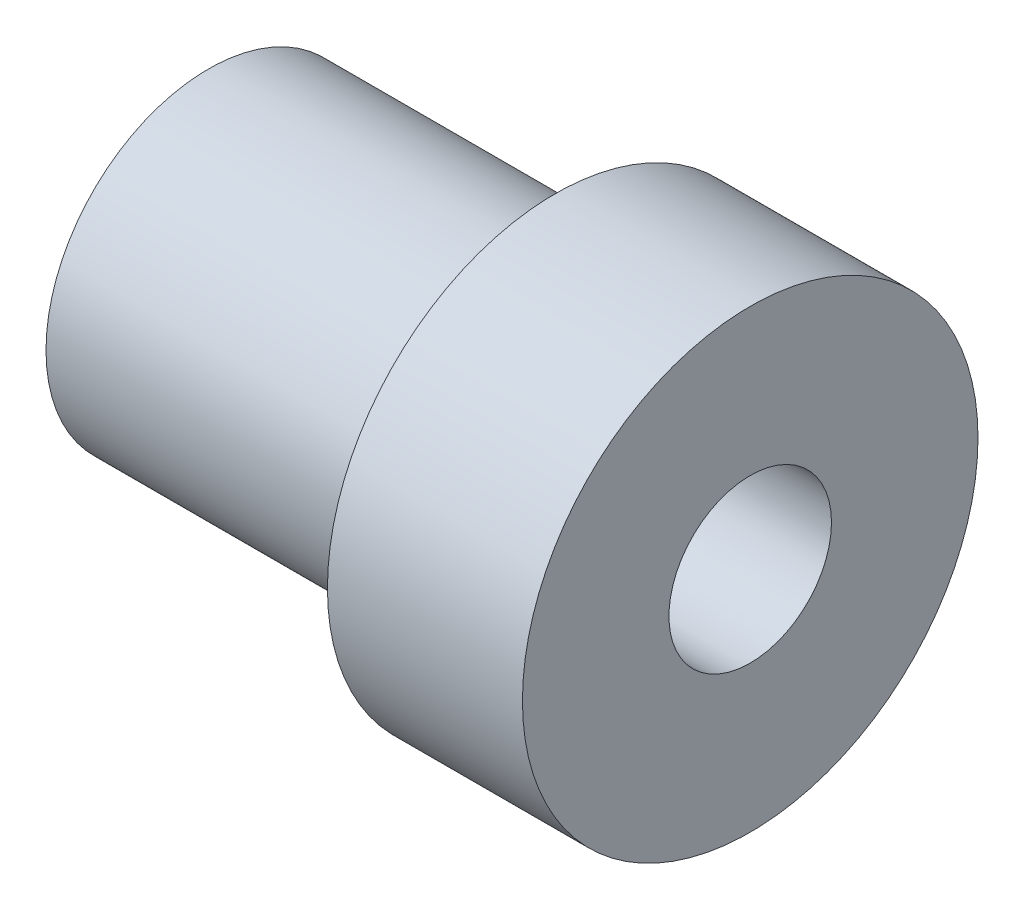
SolidWorks part; units mm, degrees
ref_plane "Front Plane" through (0, 0, 0) normal (0, 0, 1) x (1, 0, 0)
ref_plane "Top Plane" through (0, 0, 0) normal (0, 1, 0) x (1, 0, 0)
ref_plane "Right Plane" through (0, 0, 0) normal (1, 0, 0) x (0, 0, -1)
sketch "Sketch1" plane through (0, 0, 0) normal (1, 0, 0) x (0, 0, -1)
  circle A0 centre (0, 0) radius 3.9688
  dimension "D1" = 7.9375
extrude "Boss-Extrude1" add sketch "Sketch1" along normal blind 8.4667
sketch "Sketch2" plane through (8.4667, 0, 0) normal (1, 0, 0) x (0, 0, -1)
  circle A0 centre (0, 0) radius 5.5626
  dimension "D1" = 11.1252
extrude "Boss-Extrude2" add sketch "Sketch2" along normal blind 4.7625
hole_wizard "5/32 (0.15625) Diameter Hole1" positions "Sketch4" profile "Sketch3" hole size "5/32" standard "ANSI Inch"
sketch "Sketch4" plane through (13.2292, 0, 0) normal (1, 0, 0) x (0, 0, -1)
  point P0 (0, 0)
sketch "Sketch3" plane through (13.2292, 0, 0) normal (0, 1, 0) x (0, 0, -1)
  line L0 (0, 0) -> (0, 71.2963)
  line L1 (0, 71.2963) -> (1.9844, 70.104)
  line L2 (1.9844, 70.104) -> (1.9844, 0)
  line L5 (1.9844, 0) -> (0, 0)
  line L10 (0, 71.2963) -> (-1.9844, 70.104) construction
  line L11 (0, -6.35) -> (0, 107.95) construction
  dimension "Hole Dia." = 3.9688
  dimension "Hole Depth" = 70.104
  dimension "Drill Angle" = 118
